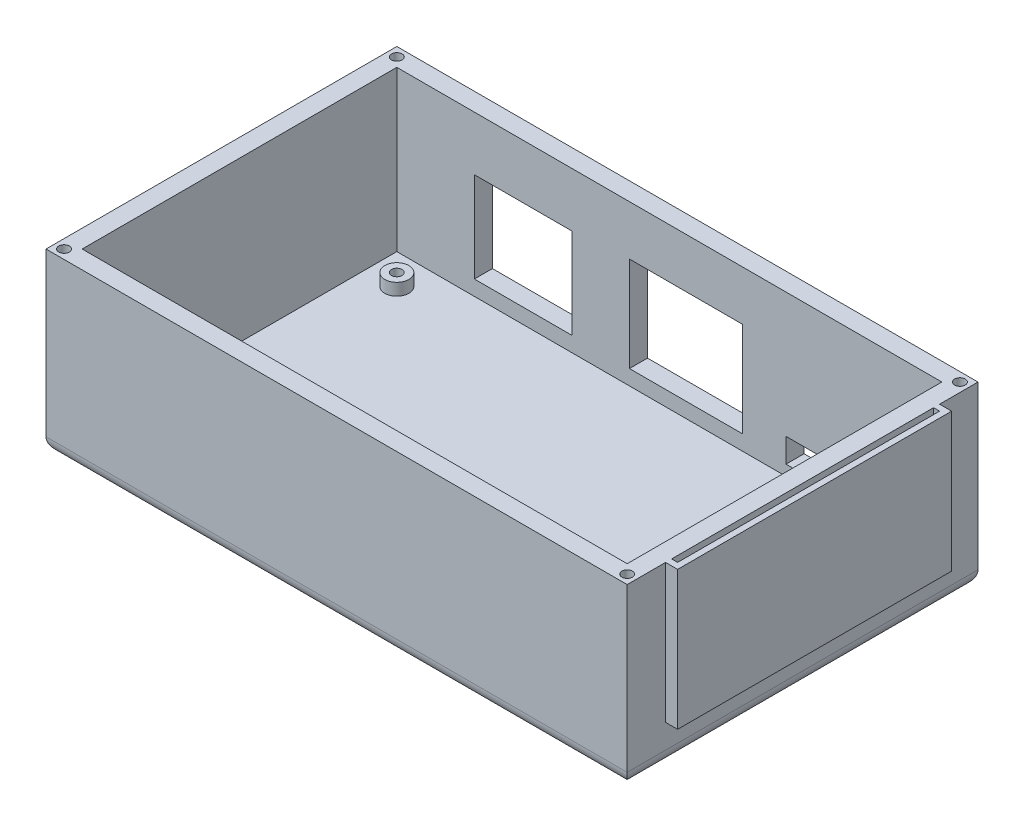
SolidWorks part; units mm, degrees
ref_plane "Front Plane" through (0, 0, 0) normal (0, 0, 1) x (1, 0, 0)
ref_plane "Top Plane" through (0, 0, 0) normal (0, 1, 0) x (1, 0, 0)
ref_plane "Right Plane" through (0, 0, 0) normal (1, 0, 0) x (0, 0, -1)
sketch "Sketch1" plane through (0, 0, 0) normal (0, 1, 0) x (1, 0, 0)
  line L1 (-85.8031, 57.8238) -> (107.1969, 57.8238)
  line L2 (-85.8031, 57.8238) -> (-85.8031, -58.6762)
  line L3 (-85.8031, -58.6762) -> (107.1969, -58.6762)
  line L4 (107.1969, 57.8238) -> (107.1969, -58.6762)
  dimension "D1" = 193
  dimension "D2" = 116.5
extrude "Boss-Extrude5" add sketch "Sketch1" along normal blind 59 contours L1 L4 L3 L2
shell "Shell4" thickness 6
sketch "Sketch6" plane through (0, 6, 0) normal (0, 1, 0) x (1, 0, 0)
  line L10 (-79.8031, 51.8238) -> (-79.8031, -52.6762) construction
  line L11 (101.1969, 51.8238) -> (101.1969, -52.6762) construction
  line L14 (-79.8031, 51.8238) -> (-79.8031, -52.6762) construction
  line L16 (-79.8031, 51.8238) -> (101.1969, 51.8238) construction
  circle A0 centre (-69.8031, 41.8238) radius 1.75
  circle A1 centre (90.1969, 41.8238) radius 1.75
  circle A2 centre (-69.8031, -38.4262) radius 1.75
  circle A3 centre (90.1969, -38.4262) radius 1.75
  circle A4 centre (-69.8031, 41.8238) radius 4
  circle A5 centre (90.1969, 41.8238) radius 4
  circle A6 centre (90.1969, -38.4262) radius 4
  circle A7 centre (-69.8031, -38.4262) radius 4
  dimension "D5" = 10
  dimension "D9" = 80.25
  dimension "D1" = 3.5
  dimension "D2" = 8
  dimension "D7" = 3.5
  dimension "D8" = 8
  dimension "D13" = 3.5
  dimension "D14" = 8
  dimension "D15" = 8
  dimension "D16" = 3.5
  dimension "D3" = 11
  dimension "D4" = 10
  dimension "D6" = 10
  dimension "D10" = 11
  dimension "D11" = 10
  dimension "D12" = 80.25
  dimension "D17" = 160
extrude "Boss-Extrude6" add sketch "Sketch6" along normal blind 4 contours A4 | A0 | A1 | A5 | A3 | A6 | A7 | A2
sketch "Sketch8" plane through (0, 0, -57.8238) normal (0, 0, -1) x (-1, 0, 0)
  line L0 (85.8031, 0) -> (-107.1969, 0) construction
  line L1 (10.0531, 41) -> (61.0531, 41)
  line L3 (10.0531, 11) -> (61.0531, 11)
  line L4 (61.0531, 41) -> (61.0531, 11)
  line L6 (-100.1969, 51.0276) -> (78.8031, 51.0276)
  line L7 (-107.1969, 59) -> (-107.1969, 0) construction
  line L8 (-85.9469, 18.5) -> (-100.1969, 18.5)
  line L10 (10.0531, 11) -> (-45.9469, 11)
  line L11 (10.0531, 41) -> (10.0531, 42.5)
  line L12 (10.0531, 42.5) -> (-45.9469, 42.5)
  line L13 (-45.9469, 25) -> (-45.9469, 42.5)
  line L14 (-45.9469, 11) -> (-63.9469, 11)
  line L16 (-45.9469, 25) -> (-63.9469, 25)
  line L17 (-63.9469, 18.5) -> (-63.9469, 25)
  line L18 (-63.9469, 11) -> (-85.9469, 11)
  line L20 (-63.9469, 18.5) -> (-85.9469, 18.5)
  line L22 (-85.9469, 11) -> (-100.1969, 11)
  line L23 (-100.1969, 18.5) -> (-100.1969, 11)
  dimension "D1" = 11
  dimension "D2" = 179
  dimension "D3" = 7
  dimension "D4" = 17.75
  dimension "D5" = 51
  dimension "D6" = 56
  dimension "D7" = 30
  dimension "D8" = 1.5
  dimension "D9" = 18
  dimension "D10" = 14
  dimension "D11" = 22
  dimension "D12" = 7.5
extrude "Cut-Extrude1" cut sketch "Sketch8" against normal blind 34 and the other way blind 38 contours L8 L23 L22 L18 L14 L10 L3 L4 L1 L11 L12 L13 L16 L17 L20
sketch "Sketch9" plane through (0, 59, 0) normal (0, 1, 0) x (1, 0, 0)
  line L0 (-85.8031, 57.8238) -> (107.1969, 57.8238) construction
  line L1 (-85.8031, 57.8238) -> (-85.8031, -58.6762) construction
  line L2 (107.1969, 57.8238) -> (107.1969, -58.6762) construction
  line L3 (-85.8031, -58.6762) -> (107.1969, -58.6762) construction
  circle A0 centre (-82.8031, 54.8238) radius 1.75
  circle A1 centre (104.1969, 54.8238) radius 1.75
  circle A2 centre (-82.8031, -55.6762) radius 1.75
  circle A3 centre (104.1969, -55.6762) radius 1.75
  dimension "D1" = 3
  dimension "D2" = 3
  dimension "D3" = 3
  dimension "D4" = 3
extrude "Cut-Extrude2" cut sketch "Sketch9" against normal blind 7
fillet "Fillet2" radius 5 4 edges at (10.6969, 0, 58.6762) (107.1969, 0, 0.4262) (10.6969, 0, -57.8238) (-85.8031, 0, 0.4262)
sketch "Sketch12" plane through (63.9469, 0, 0) normal (-1, 0, 0) x (0, 0, 1)
  line L0 (-51.8238, 25) -> (-51.8238, 18.5) construction
  line L1 (-57.8238, 18.5) -> (-51.8238, 18.5)
  line L2 (-57.8238, 18.5) -> (-57.8238, 25)
  line L3 (-57.8238, 25) -> (-51.8238, 25)
  line L4 (-51.8238, 18.5) -> (-51.8238, 25)
  line L5 (-57.8238, 25) -> (-51.8238, 25) construction
  dimension "D1" = 0
extrude "Boss-Extrude7" add sketch "Sketch12" along normal blind 18
sketch "Sketch15" plane through (100.1969, 0, 0) normal (-1, 0, 0) x (0, 0, 1)
  line L0 (-51.8238, 11) -> (-51.8238, 18.5) construction
  line L1 (-57.8238, 18.5) -> (-51.8238, 18.5)
  line L2 (-57.8238, 18.5) -> (-57.8238, 11)
  line L3 (-57.8238, 11) -> (-51.8238, 11)
  line L4 (-51.8238, 18.5) -> (-51.8238, 11)
  line L5 (-57.8238, 11) -> (-51.8238, 11) construction
  dimension "D1" = 0
extrude "Boss-Extrude8" add sketch "Sketch15" along normal blind 5
sketch "Sketch16" plane through (0, 18.5, 0) normal (0, -1, 0) x (1, 0, 0)
  line L0 (95.1969, -57.8238) -> (45.9469, -57.8238) construction
  line L1 (95.1969, -51.8238) -> (45.9469, -51.8238) construction
  line L2 (87.1969, -57.8238) -> (79.6969, -57.8238)
  line L3 (87.1969, -57.8238) -> (87.1969, -51.8238)
  line L4 (87.1969, -51.8238) -> (79.6969, -51.8238)
  line L5 (79.6969, -57.8238) -> (79.6969, -51.8238)
  line L7 (65.1969, -57.8238) -> (58.4469, -57.8238)
  line L8 (65.1969, -57.8238) -> (65.1969, -51.8238)
  line L9 (65.1969, -51.8238) -> (58.4469, -51.8238)
  line L10 (58.4469, -57.8238) -> (58.4469, -51.8238)
  line L11 (49.4469, -57.8238) -> (45.9469, -57.8238)
  line L12 (49.4469, -57.8238) -> (49.4469, -51.8238)
  line L13 (49.4469, -51.8238) -> (45.9469, -51.8238)
  line L14 (45.9469, -57.8238) -> (45.9469, -51.8238)
  point P0 (87.1969, -57.8238)
  point P1 (95.1969, -57.8238)
  point P11 (65.1969, -57.8238)
  point P16 (49.4469, -57.8238)
  dimension "D1" = 8
  dimension "D2" = 7.5
  dimension "D3" = 14.5
  dimension "D4" = 6.75
  dimension "D5" = 9
extrude "Boss-Extrude9" add sketch "Sketch16" along normal blind 7.5
sketch "Sketch17" plane through (45.9469, 0, 0) normal (-1, 0, 0) x (0, 0, 1)
  line L1 (-57.8238, 42.5) -> (-51.8238, 42.5)
  line L2 (-57.8238, 42.5) -> (-57.8238, 11)
  line L3 (-57.8238, 11) -> (-51.8238, 11)
  line L4 (-51.8238, 42.5) -> (-51.8238, 11)
  point P0 (-57.8238, 42.5)
  point P1 (-51.8238, 11)
extrude "Boss-Extrude10" add sketch "Sketch17" along normal blind 4
sketch "Sketch18" plane through (-10.0531, 0, 0) normal (1, 0, 0) x (0, 0, -1)
  line L1 (51.8238, 42.5) -> (57.8238, 42.5)
  line L2 (51.8238, 42.5) -> (51.8238, 41)
  line L3 (51.8238, 41) -> (57.8238, 41)
  line L4 (57.8238, 42.5) -> (57.8238, 41)
  point P0 (51.8238, 42.5)
  point P1 (57.8238, 41)
extrude "Boss-Extrude11" add sketch "Sketch18" along normal blind 1.5
sketch "Sketch19" plane through (0, 41, 0) normal (0, -1, 0) x (1, 0, 0)
  line L0 (-61.0531, -51.8238) -> (-8.5531, -51.8238) construction
  line L1 (-8.5531, -51.8238) -> (-8.5531, -57.8238) construction
  line L3 (-10.5531, -51.8238) -> (-8.5531, -51.8238)
  line L4 (-10.5531, -51.8238) -> (-10.5531, -57.8238)
  line L5 (-10.5531, -57.8238) -> (-8.5531, -57.8238)
  line L6 (-8.5531, -51.8238) -> (-8.5531, -57.8238)
  point P0 (-10.5531, -51.8238)
  dimension "D1" = 2
extrude "Boss-Extrude12" add sketch "Sketch19" along normal blind 30
sketch "Sketch20" plane through (0, 0, -57.8238) normal (0, 0, -1) x (-1, 0, 0)
  line L2 (-49.4469, 11) -> (-49.4469, 18.5) construction
  line L3 (-58.4469, 18.5) -> (-49.4469, 18.5)
  line L4 (-58.4469, 18.5) -> (-58.4469, 16)
  line L5 (-58.4469, 16) -> (-49.4469, 16)
  line L6 (-49.4469, 18.5) -> (-49.4469, 16)
  line L7 (-58.4469, 11) -> (-49.4469, 11) construction
  dimension "D1" = 5
extrude "Boss-Extrude13" add sketch "Sketch20" against normal blind 6
sketch "Sketch21" plane through (79.6969, 0, 0) normal (-1, 0, 0) x (0, 0, 1)
  line L1 (-57.8238, 18.5) -> (-51.8238, 18.5)
  line L2 (-57.8238, 18.5) -> (-57.8238, 11)
  line L3 (-57.8238, 11) -> (-51.8238, 11)
  line L4 (-51.8238, 18.5) -> (-51.8238, 11)
  point P0 (-57.8238, 18.5)
  point P1 (-51.8238, 11)
extrude "Cut-Extrude3" cut sketch "Sketch21" against normal blind 3
sketch "Sketch22" plane through (0, 18.5, 0) normal (0, -1, 0) x (1, 0, 0)
  line L1 (82.6969, -57.8238) -> (65.1969, -57.8238)
  line L2 (82.6969, -57.8238) -> (82.6969, -51.8238)
  line L3 (82.6969, -51.8238) -> (65.1969, -51.8238)
  line L4 (65.1969, -57.8238) -> (65.1969, -51.8238)
extrude "Cut-Extrude4" cut sketch "Sketch22" against normal blind 2
sketch "Sketch23" plane through (58.4469, 0, 0) normal (-1, 0, 0) x (0, 0, 1)
  line L1 (-57.8238, 16) -> (-51.8238, 16)
  line L2 (-57.8238, 16) -> (-57.8238, 11)
  line L3 (-57.8238, 11) -> (-51.8238, 11)
  line L4 (-51.8238, 16) -> (-51.8238, 11)
extrude "Cut-Extrude5" cut sketch "Sketch23" against normal blind 2
sketch "Sketch24" plane through (0, 16, 0) normal (0, -1, 0) x (1, 0, 0)
  line L1 (49.4469, -51.8238) -> (60.4469, -51.8238)
  line L2 (49.4469, -51.8238) -> (49.4469, -57.8238)
  line L3 (49.4469, -57.8238) -> (60.4469, -57.8238)
  line L4 (60.4469, -51.8238) -> (60.4469, -57.8238)
extrude "Cut-Extrude6" cut sketch "Sketch24" against normal blind 1.5
sketch "Sketch25" plane through (0, 11, 0) normal (0, 1, 0) x (1, 0, 0)
  line L1 (49.4469, 57.8238) -> (60.4469, 57.8238)
  line L2 (49.4469, 57.8238) -> (49.4469, 51.8238)
  line L3 (49.4469, 51.8238) -> (60.4469, 51.8238)
  line L4 (60.4469, 57.8238) -> (60.4469, 51.8238)
extrude "Cut-Extrude7" cut sketch "Sketch25" against normal blind 1.5
sketch "Sketch27" plane through (0, 11, 0) normal (0, 1, 0) x (1, 0, 0)
  line L1 (65.1969, 57.8238) -> (82.6969, 57.8238)
  line L2 (65.1969, 57.8238) -> (65.1969, 51.8238)
  line L3 (65.1969, 51.8238) -> (82.6969, 51.8238)
  line L4 (82.6969, 57.8238) -> (82.6969, 51.8238)
extrude "Cut-Extrude8" cut sketch "Sketch27" against normal blind 1.5
sketch "Sketch32" plane through (107.1969, 0, 0) normal (1, 0, 0) x (0, 0, -1)
  line L0 (57.8238, 59) -> (-58.6762, 59) construction
  line L1 (-45.9262, 59) -> (45.0738, 59)
  line L2 (-45.9262, 59) -> (-45.9262, 13)
  line L3 (-45.9262, 13) -> (45.0738, 13)
  line L4 (45.0738, 59) -> (45.0738, 13)
  line L5 (-58.6762, 5) -> (57.8238, 5) construction
  line L6 (-58.6762, 59) -> (-58.6762, 5) construction
  dimension "D1" = 91
  dimension "D2" = 8
  dimension "D3" = 12.75
extrude "Boss-Extrude15" add sketch "Sketch32" along normal blind 4
sketch "Sketch33" plane through (0, 59, 0) normal (0, 1, 0) x (1, 0, 0)
  line L0 (111.1969, -45.9262) -> (107.1969, -45.9262) construction
  line L1 (107.1969, 43.0738) -> (109.1969, 43.0738)
  line L2 (107.1969, 43.0738) -> (107.1969, -43.9262)
  line L3 (107.1969, -43.9262) -> (109.1969, -43.9262)
  line L4 (109.1969, 43.0738) -> (109.1969, -43.9262)
  line L5 (111.1969, 45.0738) -> (111.1969, -45.9262) construction
  line L6 (111.1969, 45.0738) -> (107.1969, 45.0738) construction
  line L7 (107.1969, 57.8238) -> (107.1969, 45.0738) construction
  dimension "D1" = 2
  dimension "D2" = 2
  dimension "D3" = 2
  dimension "D4" = 0
extrude "Cut-Extrude10" cut sketch "Sketch33" against normal blind 44
sketch "Sketch34" plane through (0, 11, 0) normal (0, 1, 0) x (1, 0, 0)
  line L1 (87.1969, 57.8238) -> (95.1969, 57.8238)
  line L2 (87.1969, 57.8238) -> (87.1969, 51.8238)
  line L3 (87.1969, 51.8238) -> (95.1969, 51.8238)
  line L4 (95.1969, 57.8238) -> (95.1969, 51.8238)
  point P0 (95.1969, 51.8238)
extrude "Cut-Extrude11" cut sketch "Sketch34" against normal blind 1.5
sketch "Sketch35" plane through (-10.5531, 0, 0) normal (-1, 0, 0) x (0, 0, 1)
  line L1 (-57.8238, 41) -> (-51.8238, 41)
  line L2 (-57.8238, 41) -> (-57.8238, 11)
  line L3 (-57.8238, 11) -> (-51.8238, 11)
  line L4 (-51.8238, 41) -> (-51.8238, 11)
  point P0 (-51.8238, 11)
extrude "Boss-Extrude16" add sketch "Sketch35" along normal blind 11
sketch "Sketch36" plane through (-61.0531, 0, 0) normal (1, 0, 0) x (0, 0, -1)
  line L1 (57.8238, 41) -> (51.8238, 41)
  line L2 (57.8238, 41) -> (57.8238, 11)
  line L3 (57.8238, 11) -> (51.8238, 11)
  line L4 (51.8238, 41) -> (51.8238, 11)
  point P0 (51.8238, 11)
extrude "Boss-Extrude17" add sketch "Sketch36" along normal blind 7
sketch "Sketch37" plane through (-8.5531, 0, 0) normal (1, 0, 0) x (0, 0, -1)
  line L1 (57.8238, 42.5) -> (51.8238, 42.5)
  line L2 (57.8238, 42.5) -> (57.8238, 11)
  line L3 (57.8238, 11) -> (51.8238, 11)
  line L4 (51.8238, 42.5) -> (51.8238, 11)
extrude "Boss-Extrude18" add sketch "Sketch37" along normal blind 6
sketch "Sketch38" plane through (41.9469, 0, 0) normal (-1, 0, 0) x (0, 0, 1)
  line L1 (-57.8238, 42.5) -> (-51.8238, 42.5)
  line L2 (-57.8238, 42.5) -> (-57.8238, 11)
  line L3 (-57.8238, 11) -> (-51.8238, 11)
  line L4 (-51.8238, 42.5) -> (-51.8238, 11)
extrude "Boss-Extrude19" add sketch "Sketch38" along normal blind 7
